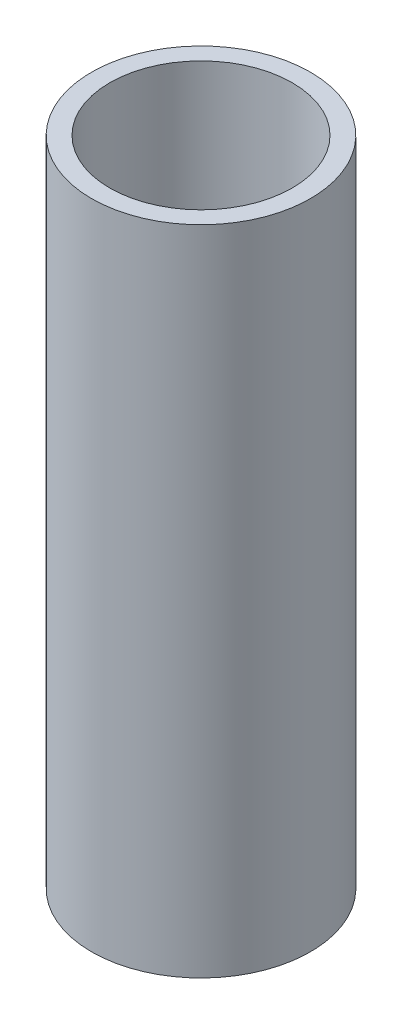
SolidWorks part; units mm, degrees
material "1.0050 (E295)"
ref_plane "Płaszczyzna przednia" through (0, 0, 0) normal (0, 0, 1) x (1, 0, 0)
ref_plane "Płaszczyzna górna" through (0, 0, 0) normal (0, 1, 0) x (1, 0, 0)
ref_plane "Płaszczyzna prawa" through (0, 0, 0) normal (1, 0, 0) x (0, 0, -1)
sketch "Szkic1" plane through (0, 0, 0) normal (0, 1, 0) x (1, 0, 0)
  circle A0 centre (0, 0) radius 12
  circle A1 centre (0, 0) radius 10
  dimension "D1" = 24
  dimension "D2" = 20
extrude "Dodanie-wyciągnięcie1" add sketch "Szkic1" along normal blind 71.5
